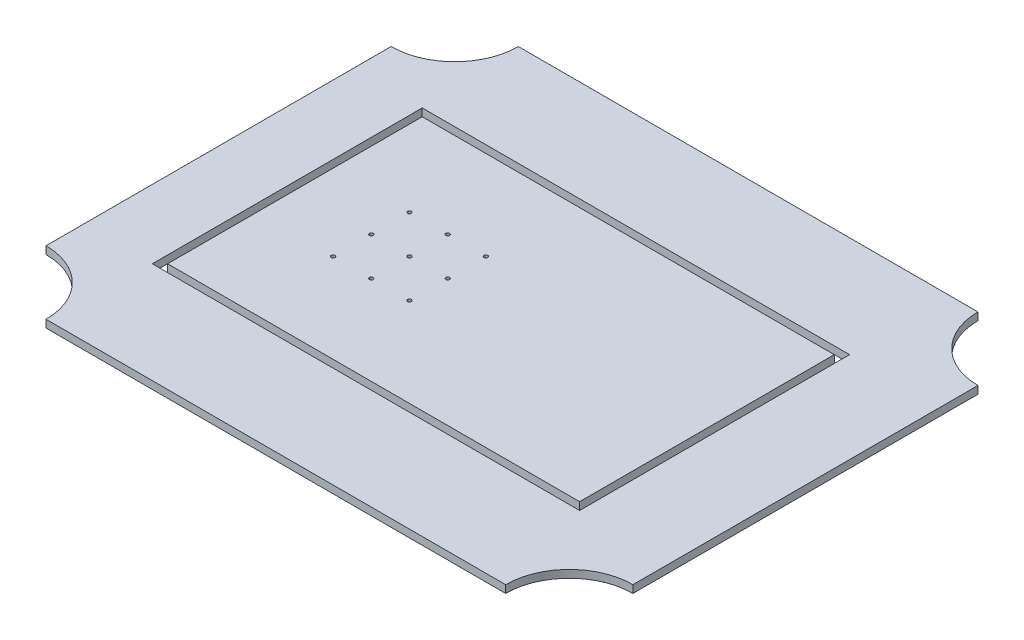
SolidWorks part; units mm, degrees
material "有机玻璃 (TM) GS 丙烯酸铸钣"
ref_plane "前视基准面" through (0, 0, 0) normal (0, 0, 1) x (1, 0, 0)
ref_plane "上视基准面" through (0, 0, 0) normal (0, 1, 0) x (1, 0, 0)
ref_plane "右视基准面" through (0, 0, 0) normal (1, 0, 0) x (0, 0, -1)
other "Configuration Table"
sketch "草图1" plane through (0, 0, 0) normal (0, 1, 0) x (1, 0, 0)
  line L0 (-195.6915, 0) -> (265.3085, 0) construction
  line L1 (-145.6915, 185.5) -> (215.3085, 185.5)
  line L2 (-195.6915, 135.5) -> (-195.6915, -135.5)
  line L3 (-145.6915, -185.5) -> (215.3085, -185.5)
  line L4 (265.3085, 135.5) -> (265.3085, -135.5)
  line L5 (-141.6915, 106) -> (193.9331, 106)
  line L6 (-135.6915, 100) -> (187.9331, 100)
  line L7 (-45.6915, 306.7081) -> (-45.6915, -288.7612) construction
  line L8 (-75.6915, 185.5) -> (-75.6915, -185.5) construction
  line L9 (265.3085, 199.7584) -> (265.3085, -200.2416) construction
  line L10 (-135.6915, 100) -> (-135.6915, -100)
  line L11 (-135.6915, -100) -> (187.9331, -100)
  line L12 (187.9331, 100) -> (187.9331, -100)
  line L13 (193.9331, 106) -> (193.9331, -106)
  line L14 (-141.6915, -106) -> (193.9331, -106)
  line L15 (-141.6915, 106) -> (-141.6915, -106)
  arc A0 (-195.6915, 135.5) -> (-145.6915, 185.5) centre (-195.6915, 185.5) ccw
  arc A1 (215.3085, 185.5) -> (265.3085, 135.5) centre (265.3085, 185.5) ccw
  arc A2 (265.3085, -135.5) -> (215.3085, -185.5) centre (265.3085, -185.5) ccw
  arc A3 (-145.6915, -185.5) -> (-195.6915, -135.5) centre (-195.6915, -185.5) ccw
  circle A4 centre (-75.6915, 0) radius 1.5
  circle A5 centre (-75.6915, 30) radius 1.5
  circle A6 centre (-45.6915, 30) radius 1.5
  circle A8 centre (-45.6915, 0) radius 1.5
  circle A11 centre (-45.6915, -30) radius 1.5
  circle A12 centre (-75.6915, -30) radius 1.5
  circle A13 centre (-15.6915, -30) radius 1.5
  circle A14 centre (-15.6915, 0) radius 1.5
  circle A15 centre (-15.6915, 30) radius 1.5
  point P15 (0, 0)
  point P38 (0, 0)
  dimension "D3" = 100
  dimension "D6" = 3
  dimension "D13" = 3
  dimension "D1" = 371
  dimension "D2" = 461
  dimension "D4" = 30
  dimension "D5" = 150
  dimension "D7" = 60
  dimension "D8" = 60
  dimension "D9" = 200
  dimension "D10" = 323.6246
  dimension "D11" = 60
  dimension "D12" = 6
extrude "凸台-拉伸1" add sketch "草图1" along normal blind 6 contours A3 L3 A2 L4 A1 L1 A0 L2 L15 L5 L13 L14 | L12 L6 L10 L11 A14 A13 A11 A8 A6 A5 A4 A12 A15
